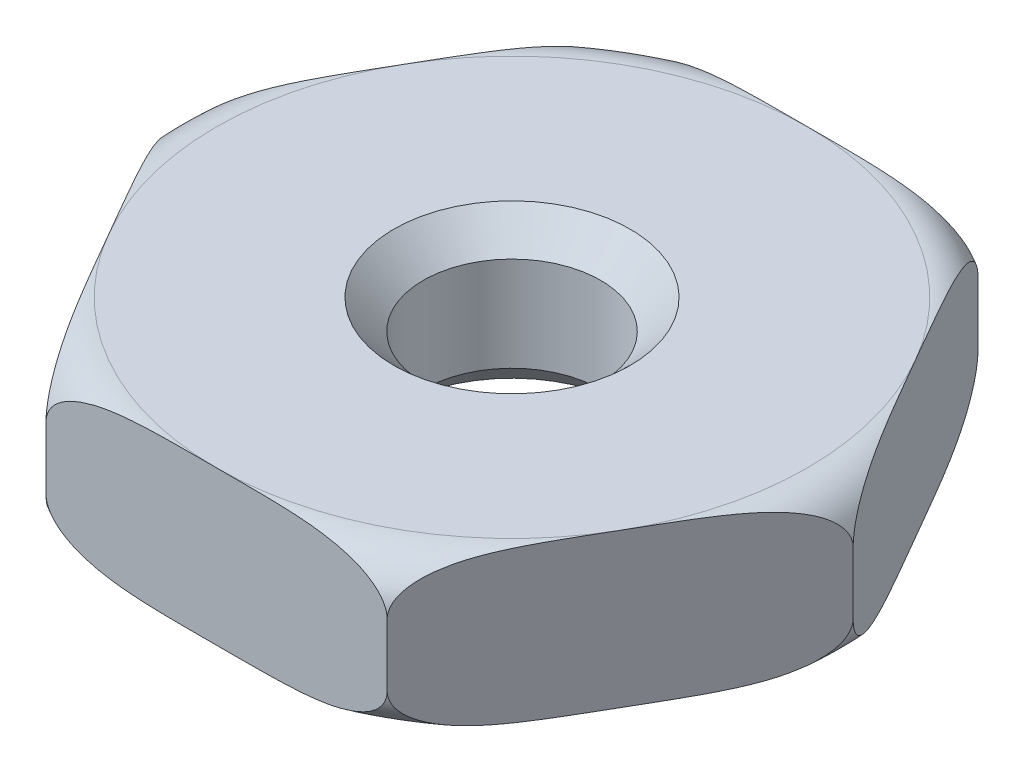
SolidWorks part; units mm, degrees
ref_plane "Front Plane" through (0, 0, 0) normal (0, 0, 1) x (1, 0, 0)
ref_plane "Top Plane" through (0, 0, 0) normal (0, 1, 0) x (1, 0, 0)
ref_plane "Right Plane" through (0, 0, 0) normal (1, 0, 0) x (0, 0, -1)
sketch "Sketch1" plane through (0, 0, 0) normal (0, 1, 0) x (1, 0, 0)
  line L0 (-13.3061, 0) -> (13.3061, 0) construction
  line L1 (1.4434, 0) -> (0.7217, 1.25)
  line L2 (0.7217, 1.25) -> (-0.7217, 1.25)
  line L3 (-0.7217, 1.25) -> (-1.4434, 0)
  line L4 (-1.4434, 0) -> (-0.7217, -1.25)
  line L5 (-0.7217, -1.25) -> (0.7217, -1.25)
  line L6 (0.7217, -1.25) -> (1.4434, 0)
  circle A0 centre (0, 0) radius 1.25 construction
  dimension "D1" = 2.5
extrude "Boss-Extrude1" add sketch "Sketch1" along normal mid plane 0.65
sketch "Sketch3" plane through (0, 0, 0) normal (0, 0, 1) x (1, 0, 0)
  line L0 (-1.4434, 0.325) -> (-1.4434, -0.325) construction
  line L1 (-1.4434, 0.325) -> (-1.4434, 0.1316)
  line L2 (-1.4434, 0.325) -> (-0.7217, 0.325) construction
  line L3 (-1.4434, 0.325) -> (-1.25, 0.325)
  line L4 (0, 0) -> (0, -1.4354) construction
  line L6 (0, -0.3575) -> (0, 0.3575) construction
  arc A0 (-1.4434, 0.1316) -> (-1.25, 0.325) centre (-1.25, 0.1316) cw
  dimension "D2" = 2.5
revolve "Cut-Revolve1" cut sketch "Sketch3" angle 360 about L4
mirror "Mirror1" about plane through (0, 0, 0) normal (0, 1, 0) of "Cut-Revolve1"
sketch "Sketch6" plane through (0, 0.325, 0) normal (0, 1, 0) x (1, 0, 0)
  circle A0 centre (0, 0) radius 0.375
  dimension "D1" = 0.75
extrude "Cut-Extrude1" cut sketch "Sketch6" against normal through all
cosmetic thread "Cosmetic Thread1" parameters "D2"=1
chamfer "Chamfer1" distance 0.125 angle 45 2 edges at (0, -0.325, 0.375) (0, 0.325, 0.375)
equation "\"D2@Sketch3\"=\"D1@Sketch1\""
